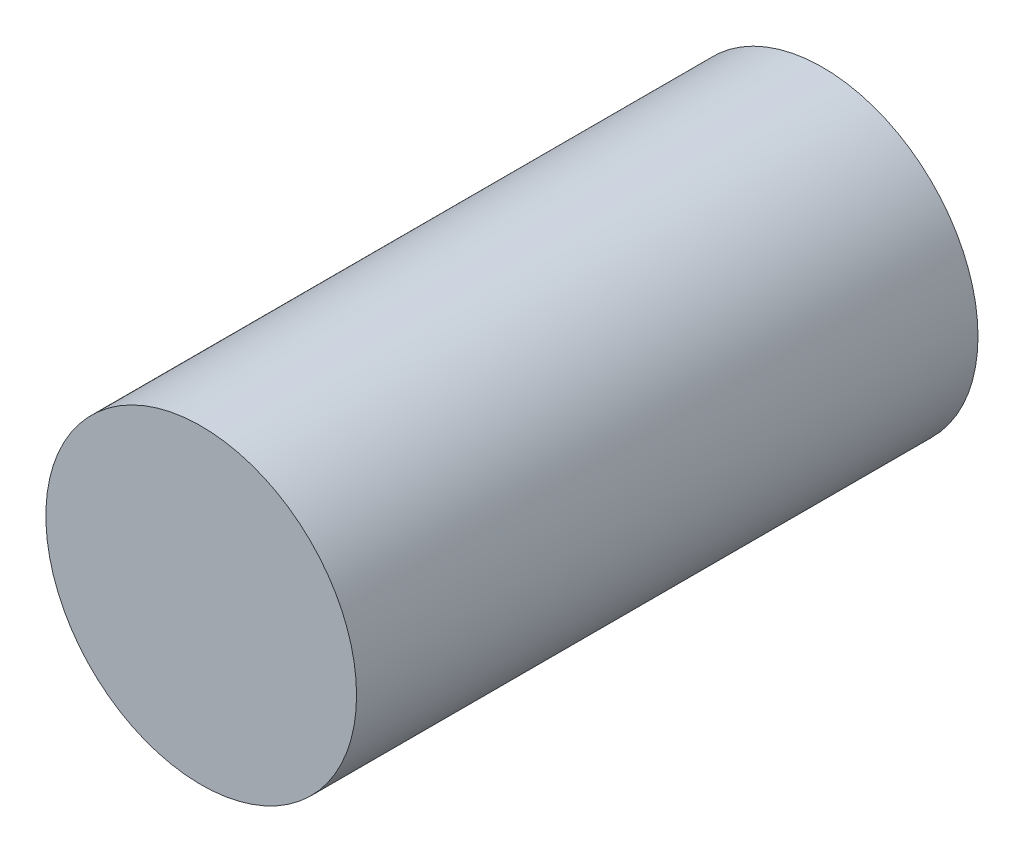
SolidWorks part; units mm, degrees
ref_plane "Plano frontal" through (0, 0, 0) normal (0, 0, 1) x (1, 0, 0)
ref_plane "Plano superior" through (0, 0, 0) normal (0, 1, 0) x (1, 0, 0)
ref_plane "Plano direito" through (0, 0, 0) normal (1, 0, 0) x (0, 0, -1)
sketch "Esboço1" plane through (0, 0, 0) normal (0, 0, 1) x (1, 0, 0)
  circle A0 centre (0, 0) radius 1
  dimension "D1" = 2
extrude "Ressalto-extrusão1" add sketch "Esboço1" along normal blind 4
